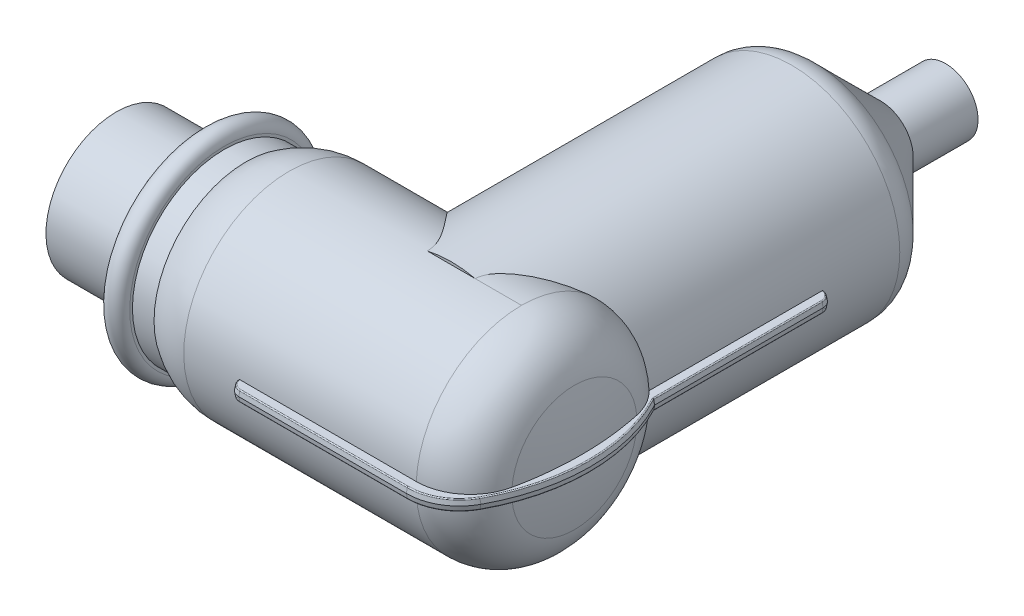
SolidWorks part; units mm, degrees
ref_plane "Front Plane" through (0, 0, 0) normal (0, 0, 1) x (1, 0, 0)
ref_plane "Top Plane" through (0, 0, 0) normal (0, 1, 0) x (1, 0, 0)
ref_plane "Right Plane" through (0, 0, 0) normal (1, 0, 0) x (0, 0, -1)
sketch "Sketch1" plane through (0, 0, 0) normal (0, 0, 1) x (1, 0, 0)
  line L0 (8, 6.5) -> (8, 8.75)
  line L2 (10, 8.75) -> (10, 8.5)
  line L3 (10, 8.5) -> (12, 8.5)
  line L4 (0, 0) -> (43, 0)
  line L5 (37.5, 9.75) -> (16, 9.75)
  line L6 (0, 0) -> (-5.7927, 0) construction
  line L7 (43, 0) -> (43, 7.3633) construction
  line L8 (8, 6.5) -> (0, 6.5)
  line L9 (0, 6.5) -> (0, 0)
  arc A0 (8, 8.75) -> (10, 8.75) centre (9, 8.75) cw
  arc A1 (16, 9.75) -> (12, 8.5) centre (16, 2.725) ccw
  arc A2 (43, 0) -> (42.3904, 5.7911) centre (15.1875, 0) ccw
  arc A3 (37.5, 9.75) -> (42.3904, 5.7911) centre (37.5, 4.75) cw
  dimension "D9" = 5
  dimension "D1" = 2
  dimension "D2" = 17.5
  dimension "D3" = 4
  dimension "D4" = 8
  dimension "D5" = 17
  dimension "D6" = 35
  dimension "D7" = 29.5
  dimension "D8" = 19.5
  dimension "D10" = 13
  dimension "D11" = 8
revolve "Revolve1" add sketch "Sketch1" angle 360 about L6
sketch "Sketch2" plane through (0, 0, 0) normal (0, 1, 0) x (1, 0, 0)
  line L0 (31, 0) -> (31, -17.9723) construction
  line L1 (31, 0) -> (0, 0) construction
  line L2 (41, 0) -> (31, 0)
  line L3 (31, 0) -> (31, 45.7426)
  line L4 (31, 45.7426) -> (34, 45.7426)
  line L5 (34, 45.7426) -> (34, 39.7426)
  line L6 (34, 39.7426) -> (40.1213, 33.6213)
  line L7 (41, 31.5) -> (41, 0)
  arc A0 (40.1213, 33.6213) -> (41, 31.5) centre (38, 31.5) cw
  dimension "D6" = 6
  dimension "D5" = 3
  dimension "D1" = 31
  dimension "D2" = 45
  dimension "D3" = 31.5
  dimension "D4" = 20
  dimension "D8" = 6
revolve "Revolve2" add sketch "Sketch2" angle 360 about L0
sketch "Sketch3" plane through (0, 0, 0) normal (0, 1, 0) x (1, 0, 0)
  line L0 (37.5, 6.1084) -> (37.5, -9.75) construction
  line L1 (40.9, 7.661) -> (40.9, 24.5)
  line L2 (0, 0) -> (43, 0) construction
  line L3 (21, -9.65) -> (37.5, -9.65)
  line L4 (31, 0) -> (31, 45.7426) construction
  line L5 (21.1, 9.65) -> (18, 9.65)
  line L7 (21.1, 24.5) -> (21.1, 9.65)
  line L8 (21, 31.5) -> (41, 31.5) construction
  line L9 (16, -9.75) -> (16, 9.75) construction
  line L10 (22, -10.65) -> (37.5, -10.65)
  line L11 (41.9, 7.9136) -> (41.9, 23.5)
  line L12 (20.1, 23.5) -> (20.1, 10.65)
  line L13 (20.1, 10.65) -> (19, 10.65)
  line L14 (41.9, 7.9136) -> (41.9, 24.5) construction
  line L15 (20.1, 24.5) -> (20.1, 10.65) construction
  line L16 (20.1, 10.65) -> (18, 10.65) construction
  line L17 (21, -10.65) -> (37.5, -10.65) construction
  line L18 (31, 0) -> (0, 0) construction
  arc A0 (40.9231, -7.6187) -> (40.9, 7.661) centre (26.9673, 0) ccw construction
  arc A1 (40.9231, -7.6187) -> (40.9, 7.661) centre (26.9673, 0) ccw
  arc A3 (37.5, -9.65) -> (40.9231, -7.6187) centre (37.5, -5.75) ccw
  arc A4 (37.5, -10.65) -> (41.8008, -8.0979) centre (37.5, -5.75) ccw
  arc A5 (41.8008, -8.0979) -> (41.9, 7.9136) centre (26.9673, 0) ccw
  arc A6 (41.9, 23.5) -> (40.9, 24.5) centre (40.9, 23.5) ccw
  arc A7 (20.1, 23.5) -> (21.1, 24.5) centre (21.1, 23.5) cw
  arc A8 (19, 10.65) -> (18, 9.65) centre (19, 9.65) ccw
  arc A9 (22, -10.65) -> (21, -9.65) centre (22, -9.65) cw
  dimension "D11" = 3.9
  dimension "D12" = 15.9
  dimension "D1" = 7
  dimension "D2" = 7
  dimension "D3" = 2
  dimension "D4" = 5
  dimension "D7" = 9.9
  dimension "D8" = 9.65
  dimension "D9" = 9.9
  dimension "D10" = 9.65
  dimension "D5" = 1
  dimension "D6" = 1
extrude "Boss-Extrude1" add sketch "Sketch3" along normal mid plane 1 draft 10
fillet "Fillet1" radius 0.1 24 edges at (20.4248, 0.5, -24.1128) (20.4248, -0.5, -24.1128) (20.1882, 0.5, -17.0309) (20.1882, -0.5, -17.0309) (18.3872, -0.5, -10.3252) (19.5941, 0.5, -10.5618) (41.5752, 0.5, -24.1128) (21.3872, 0.5, 10.3252) (29.75, 0.5, 10.5618) (39.9555, 0.5, 9.8881) (41.5752, -0.5, -24.1128) (43.7789, -0.5, 0.0932) (39.9555, -0.5, 9.8881) (29.75, -0.5, 10.5618) (19.5941, -0.5, -10.5618) (20.1441, -0.25, -10.6059) (20.1441, 0.25, -10.6059) (18.3872, 0.5, -10.3252) (41.8118, 0.5, -15.6958) (43.7789, 0.5, 0.0932) (41.8118, -0.5, -15.6958) (21.3872, -0.5, 10.3252)
